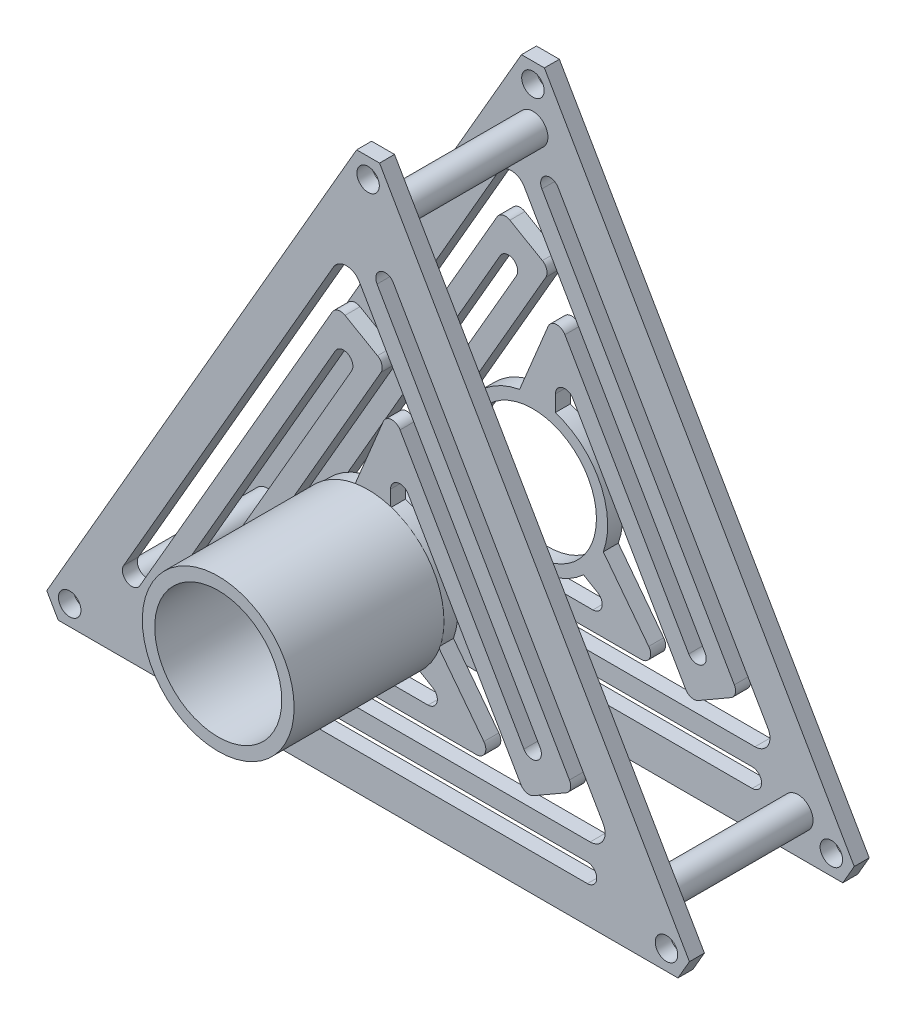
SolidWorks part; units mm, degrees
ref_plane "Front Plane" through (0, 0, 0) normal (0, 0, 1) x (1, 0, 0)
ref_plane "Top Plane" through (0, 0, 0) normal (0, 1, 0) x (1, 0, 0)
ref_plane "Right Plane" through (0, 0, 0) normal (1, 0, 0) x (0, 0, -1)
sketch "Sketch2" plane through (0, 0, 0) normal (0, 0, 1) x (1, 0, 0)
  line L0 (-1.53, 48.6355) -> (1.53, 48.6355)
  line L1 (1.53, 48.6355) -> (42.8846, -22.9927)
  line L2 (42.8846, -22.9927) -> (41.3546, -25.6427)
  line L3 (41.3546, -25.6427) -> (-41.3546, -25.6427)
  line L4 (-41.3546, -25.6427) -> (-42.8845, -22.9927)
  line L5 (-42.8845, -22.9927) -> (-1.53, 48.6355)
  line L7 (-41.1236, -23.7427) -> (-38.5255, -22.2427)
  line L8 (8.6257, -8.4442) -> (6.7534, -7.3449)
  line L9 (8.0007, -10.7767) -> (-22.0968, -10.7767)
  line L10 (-18.5968, -15.7767) -> (29.6355, -15.7767)
  line L11 (15.4531, -11.2658) -> (9.3926, -3.3669)
  line L12 (-23.3468, -12.0267) -> (-23.3468, -17.0267)
  line L13 (-22.0968, -18.2767) -> (29.2646, -18.2767)
  line L14 (29.2646, -20.7767) -> (-26.7487, -20.7767)
  line L15 (14.4613, -13.2767) -> (-18.5968, -13.2767)
  line L17 (-32.6255, -14.9556) -> (-4.6188, 33.5534)
  line L18 (-4.7797, 28.2747) -> (-30.4604, -16.2056)
  line L19 (1.258, 26.2323) -> (-3.0722, 28.7323)
  line L20 (-13.3333, -1.5405) -> (1.7155, 24.5247)
  line L21 (-18.7286, -5.8855) -> (-2.1996, 22.7436)
  line L22 (-4.3646, 23.9936) -> (-28.4808, -17.7767)
  line L23 (-17.483, -7.7498) -> (-7.6121, -6.4508)
  line L24 (-11.6257, -3.248) -> (-9.7376, -2.1762)
  line L25 (3.3608, 35.7323) -> (31.3675, -12.7767)
  line L26 (26.8765, -9.998) -> (1.1958, 34.4823)
  line L27 (22.0888, -14.2056) -> (26.419, -11.7056)
  line L28 (5.3325, 12.3172) -> (20.3813, -13.748)
  line L29 (4.2673, 19.1622) -> (20.7964, -9.4669)
  line L30 (22.9614, -8.2169) -> (-1.1547, 33.5534)
  line L31 (2.0299, 19.0156) -> (-1.7805, 9.8176)
  line L32 (3, 11.6922) -> (2.9842, 9.5211)
  circle A0 centre (-39.8246, -22.9927) radius 1.5
  circle A1 centre (0, 0) radius 8.4762
  arc A2 (-1.7805, 9.8176) -> (-9.7376, -2.1762) centre (0, 0) ccw
  arc A3 (8.6257, -8.4442) -> (8.0007, -10.7767) centre (7.9916, -9.5243) cw
  arc A4 (-22.0968, -10.7767) -> (-23.3468, -12.0267) centre (-22.0968, -12.0267) ccw
  arc A5 (-23.3468, -17.0267) -> (-22.0968, -18.2767) centre (-22.0968, -17.0267) ccw
  arc A6 (29.2646, -18.2767) -> (29.2646, -20.7767) centre (29.2646, -19.5267) cw
  circle A7 centre (0, 45.9855) radius 1.5
  arc A8 (15.4531, -11.2658) -> (14.4613, -13.2767) centre (14.4613, -12.0267) cw
  arc A9 (-18.5968, -13.2767) -> (-18.5968, -15.7767) centre (-18.5968, -14.5267) ccw
  arc A10 (-30.4604, -16.2056) -> (-32.6255, -14.9556) centre (-31.5429, -15.5806) cw
  arc A11 (-3.0722, 28.7323) -> (-4.7797, 28.2747) centre (-3.6972, 27.6497) ccw
  arc A12 (1.7155, 24.5247) -> (1.258, 26.2323) centre (0.633, 25.1497) ccw
  arc A13 (-2.1996, 22.7436) -> (-4.3646, 23.9936) centre (-3.2821, 23.3686) ccw
  arc A14 (-17.483, -7.7498) -> (-18.7286, -5.8855) centre (-17.6461, -6.5105) cw
  arc A15 (-11.6257, -3.248) -> (-13.3333, -1.5405) centre (-12.2441, -2.1588) cw
  circle A16 centre (39.8246, -22.9927) radius 1.5
  arc A17 (1.1958, 34.4823) -> (3.3608, 35.7323) centre (2.2783, 35.1073) cw
  arc A18 (26.419, -11.7056) -> (26.8765, -9.998) centre (25.794, -10.623) ccw
  arc A19 (20.3813, -13.748) -> (22.0888, -14.2056) centre (21.4638, -13.123) ccw
  arc A20 (20.7964, -9.4669) -> (22.9614, -8.2169) centre (21.8789, -8.8419) ccw
  arc A21 (2.0299, 19.0156) -> (4.2673, 19.1622) centre (3.1848, 18.5372) cw
  arc A22 (3, 11.6922) -> (5.3325, 12.3172) centre (4.2524, 11.6831) cw
  arc A23 (-26.7487, -20.7767) -> (-28.4808, -17.7767) centre (-26.7487, -18.7767) cw
  arc A24 (29.6355, -15.7767) -> (31.3675, -12.7767) centre (29.6355, -13.7767) ccw
  arc A25 (-4.6188, 33.5534) -> (-1.1547, 33.5534) centre (-2.8868, 32.5534) cw
  arc A26 (-7.6121, -6.4508) -> (6.7534, -7.3449) centre (0, 0) ccw
  arc A27 (9.3926, -3.3669) -> (2.9842, 9.5211) centre (0, 0) ccw
  point P31 (-90.3022, 1.3118)
  point P112 (0, 0)
  dimension "D2" = 2
  dimension "D3" = 2
  dimension "D4" = 2
  dimension "D1" = 3
extrude "Boss-Extrude1" add sketch "Sketch2" along normal blind 2 contours L5 L4 L3 L2 L1 L0 A16 A7 A1 A0 L17 A25 L30 A20 L29 A21 L31 A2 L24 A15 L20 A12 L19 A11 L18 A10 L23 A26 L8 A3 L9 A4 L12 A5 L13 A6 L14 A23 L22 A13 L21 A14 L11
sketch "Sketch3" plane through (0, 0, 2) normal (0, 0, 1) x (1, 0, 0)
  line L0 (-1.53, 48.6355) -> (1.53, 48.6355)
  line L1 (1.53, 48.6355) -> (42.8846, -22.9927)
  line L2 (42.8846, -22.9927) -> (41.3546, -25.6427)
  line L3 (41.3546, -25.6427) -> (-41.3546, -25.6427)
  line L4 (-41.3546, -25.6427) -> (-42.8845, -22.9927)
  line L5 (-42.8845, -22.9927) -> (-1.53, 48.6355)
  line L6 (-41.1236, -23.7427) -> (-38.5255, -22.2427)
  line L7 (8.6257, -8.4442) -> (6.7534, -7.3449)
  line L8 (8.0007, -10.7767) -> (-22.0968, -10.7767)
  line L9 (-18.5968, -15.7767) -> (29.6355, -15.7767)
  line L10 (15.4531, -11.2658) -> (9.3926, -3.3669)
  line L11 (-23.3468, -12.0267) -> (-23.3468, -17.0267)
  line L12 (-22.0968, -18.2767) -> (29.2646, -18.2767)
  line L13 (29.2646, -20.7767) -> (-26.7487, -20.7767)
  line L14 (14.4613, -13.2767) -> (-18.5968, -13.2767)
  line L15 (-32.6255, -14.9556) -> (-4.6188, 33.5534)
  line L16 (-4.7797, 28.2747) -> (-30.4604, -16.2056)
  line L17 (1.258, 26.2323) -> (-3.0722, 28.7323)
  line L18 (-13.3333, -1.5405) -> (1.7155, 24.5247)
  line L19 (-18.7286, -5.8855) -> (-2.1996, 22.7436)
  line L20 (-4.3646, 23.9936) -> (-28.4808, -17.7767)
  line L21 (-17.483, -7.7498) -> (-7.6121, -6.4508)
  line L22 (-11.6257, -3.248) -> (-9.7376, -2.1762)
  line L23 (3.3608, 35.7323) -> (31.3675, -12.7767)
  line L24 (26.8765, -9.998) -> (1.1958, 34.4823)
  line L25 (22.0888, -14.2056) -> (26.419, -11.7056)
  line L26 (5.3325, 12.3172) -> (20.3813, -13.748)
  line L27 (4.2673, 19.1622) -> (20.7964, -9.4669)
  line L28 (22.9614, -8.2169) -> (-1.1547, 33.5534)
  line L29 (2.0299, 19.0156) -> (-1.7805, 9.8176)
  line L30 (3, 11.6922) -> (2.9842, 9.5211)
  circle A2 centre (-39.8246, -22.9927) radius 1.5
  circle A3 centre (0, 0) radius 8.4762
  arc A4 (-1.7805, 9.8176) -> (-9.7376, -2.1762) centre (0, 0) ccw
  arc A5 (8.6257, -8.4442) -> (8.0007, -10.7767) centre (7.9916, -9.5243) cw
  arc A6 (-22.0968, -10.7767) -> (-23.3468, -12.0267) centre (-22.0968, -12.0267) ccw
  arc A7 (-23.3468, -17.0267) -> (-22.0968, -18.2767) centre (-22.0968, -17.0267) ccw
  arc A8 (29.2646, -18.2767) -> (29.2646, -20.7767) centre (29.2646, -19.5267) cw
  circle A9 centre (0, 45.9855) radius 1.5
  arc A10 (15.4531, -11.2658) -> (14.4613, -13.2767) centre (14.4613, -12.0267) cw
  arc A11 (-18.5968, -13.2767) -> (-18.5968, -15.7767) centre (-18.5968, -14.5267) ccw
  arc A12 (-30.4604, -16.2056) -> (-32.6255, -14.9556) centre (-31.5429, -15.5806) cw
  arc A13 (-3.0722, 28.7323) -> (-4.7797, 28.2747) centre (-3.6972, 27.6497) ccw
  arc A14 (1.7155, 24.5247) -> (1.258, 26.2323) centre (0.633, 25.1497) ccw
  arc A15 (-2.1996, 22.7436) -> (-4.3646, 23.9936) centre (-3.2821, 23.3686) ccw
  arc A16 (-17.483, -7.7498) -> (-18.7286, -5.8855) centre (-17.6461, -6.5105) cw
  arc A17 (-11.6257, -3.248) -> (-13.3333, -1.5405) centre (-12.2441, -2.1588) cw
  circle A18 centre (39.8246, -22.9927) radius 1.5
  arc A19 (1.1958, 34.4823) -> (3.3608, 35.7323) centre (2.2783, 35.1073) cw
  arc A20 (26.419, -11.7056) -> (26.8765, -9.998) centre (25.794, -10.623) ccw
  arc A21 (20.3813, -13.748) -> (22.0888, -14.2056) centre (21.4638, -13.123) ccw
  arc A22 (20.7964, -9.4669) -> (22.9614, -8.2169) centre (21.8789, -8.8419) ccw
  arc A23 (2.0299, 19.0156) -> (4.2673, 19.1622) centre (3.1848, 18.5372) cw
  arc A24 (3, 11.6922) -> (5.3325, 12.3172) centre (4.2524, 11.6831) cw
  arc A25 (-26.7487, -20.7767) -> (-28.4808, -17.7767) centre (-26.7487, -18.7767) cw
  arc A26 (29.6355, -15.7767) -> (31.3675, -12.7767) centre (29.6355, -13.7767) ccw
  arc A27 (-4.6188, 33.5534) -> (-1.1547, 33.5534) centre (-2.8868, 32.5534) cw
  arc A28 (-7.6121, -6.4508) -> (6.7534, -7.3449) centre (0, 0) ccw
  arc A29 (9.3926, -3.3669) -> (2.9842, 9.5211) centre (0, 0) ccw
  circle A30 centre (-35.3834, -20.4286) radius 2
  circle A31 centre (0, 40.8573) radius 2
  circle A32 centre (35.3834, -20.4286) radius 2
  point P89 (0, 0)
  point P95 (0, 0)
  dimension "D1" = 2
  dimension "D2" = 2
  dimension "D3" = 2
extrude "Boss-Extrude4" add sketch "Sketch3" along normal blind 20 contours A30 | A32 | A31
sketch "Sketch5" plane through (0, 0, 22) normal (0, 0, 1) x (1, 0, 0)
  line L0 (-1.53, 48.6355) -> (1.53, 48.6355)
  line L1 (1.53, 48.6355) -> (42.8846, -22.9927)
  line L2 (42.8846, -22.9927) -> (41.3546, -25.6427)
  line L3 (41.3546, -25.6427) -> (-41.3546, -25.6427)
  line L4 (-41.3546, -25.6427) -> (-42.8845, -22.9927)
  line L5 (-42.8845, -22.9927) -> (-1.53, 48.6355)
  line L6 (-41.1236, -23.7427) -> (-38.5255, -22.2427)
  line L7 (8.6257, -8.4442) -> (6.7534, -7.3449)
  line L8 (8.0007, -10.7767) -> (-22.0968, -10.7767)
  line L9 (-18.5968, -15.7767) -> (29.6355, -15.7767)
  line L10 (15.4531, -11.2658) -> (9.3926, -3.3669)
  line L11 (-23.3468, -12.0267) -> (-23.3468, -17.0267)
  line L12 (-22.0968, -18.2767) -> (29.2646, -18.2767)
  line L13 (29.2646, -20.7767) -> (-26.7487, -20.7767)
  line L14 (14.4613, -13.2767) -> (-18.5968, -13.2767)
  line L15 (-32.6255, -14.9556) -> (-4.6188, 33.5534)
  line L16 (-4.7797, 28.2747) -> (-30.4604, -16.2056)
  line L17 (1.258, 26.2323) -> (-3.0722, 28.7323)
  line L18 (-13.3333, -1.5405) -> (1.7155, 24.5247)
  line L19 (-18.7286, -5.8855) -> (-2.1996, 22.7436)
  line L20 (-4.3646, 23.9936) -> (-28.4808, -17.7767)
  line L21 (-17.483, -7.7498) -> (-7.6121, -6.4508)
  line L22 (-11.6257, -3.248) -> (-9.7376, -2.1762)
  line L23 (3.3608, 35.7323) -> (31.3675, -12.7767)
  line L24 (26.8765, -9.998) -> (1.1958, 34.4823)
  line L25 (22.0888, -14.2056) -> (26.419, -11.7056)
  line L26 (5.3325, 12.3172) -> (20.3813, -13.748)
  line L27 (4.2673, 19.1622) -> (20.7964, -9.4669)
  line L28 (22.9614, -8.2169) -> (-1.1547, 33.5534)
  line L29 (2.0299, 19.0156) -> (-1.7805, 9.8176)
  line L30 (3, 11.6922) -> (2.9842, 9.5211)
  circle A0 centre (-39.8246, -22.9927) radius 1.5
  circle A1 centre (0, 0) radius 8.4762
  arc A2 (-1.7805, 9.8176) -> (-9.7376, -2.1762) centre (0, 0) ccw
  arc A3 (8.6257, -8.4442) -> (8.0007, -10.7767) centre (7.9916, -9.5243) cw
  arc A4 (-22.0968, -10.7767) -> (-23.3468, -12.0267) centre (-22.0968, -12.0267) ccw
  arc A5 (-23.3468, -17.0267) -> (-22.0968, -18.2767) centre (-22.0968, -17.0267) ccw
  arc A6 (29.2646, -18.2767) -> (29.2646, -20.7767) centre (29.2646, -19.5267) cw
  circle A7 centre (0, 45.9855) radius 1.5
  arc A8 (15.4531, -11.2658) -> (14.4613, -13.2767) centre (14.4613, -12.0267) cw
  arc A9 (-18.5968, -13.2767) -> (-18.5968, -15.7767) centre (-18.5968, -14.5267) ccw
  arc A10 (-30.4604, -16.2056) -> (-32.6255, -14.9556) centre (-31.5429, -15.5806) cw
  arc A11 (-3.0722, 28.7323) -> (-4.7797, 28.2747) centre (-3.6972, 27.6497) ccw
  arc A12 (1.7155, 24.5247) -> (1.258, 26.2323) centre (0.633, 25.1497) ccw
  arc A13 (-2.1996, 22.7436) -> (-4.3646, 23.9936) centre (-3.2821, 23.3686) ccw
  arc A14 (-17.483, -7.7498) -> (-18.7286, -5.8855) centre (-17.6461, -6.5105) cw
  arc A15 (-11.6257, -3.248) -> (-13.3333, -1.5405) centre (-12.2441, -2.1588) cw
  circle A16 centre (39.8246, -22.9927) radius 1.5
  arc A17 (1.1958, 34.4823) -> (3.3608, 35.7323) centre (2.2783, 35.1073) cw
  arc A18 (26.419, -11.7056) -> (26.8765, -9.998) centre (25.794, -10.623) ccw
  arc A19 (20.3813, -13.748) -> (22.0888, -14.2056) centre (21.4638, -13.123) ccw
  arc A20 (20.7964, -9.4669) -> (22.9614, -8.2169) centre (21.8789, -8.8419) ccw
  arc A21 (2.0299, 19.0156) -> (4.2673, 19.1622) centre (3.1848, 18.5372) cw
  arc A22 (3, 11.6922) -> (5.3325, 12.3172) centre (4.2524, 11.6831) cw
  arc A23 (-26.7487, -20.7767) -> (-28.4808, -17.7767) centre (-26.7487, -18.7767) cw
  arc A24 (29.6355, -15.7767) -> (31.3675, -12.7767) centre (29.6355, -13.7767) ccw
  arc A25 (-4.6188, 33.5534) -> (-1.1547, 33.5534) centre (-2.8868, 32.5534) cw
  arc A26 (-7.6121, -6.4508) -> (6.7534, -7.3449) centre (0, 0) ccw
  arc A27 (9.3926, -3.3669) -> (2.9842, 9.5211) centre (0, 0) ccw
  circle A28 centre (-35.3834, -20.4286) radius 2
  circle A29 centre (0, 40.8573) radius 2
  circle A30 centre (35.3834, -20.4286) radius 2
  point P86 (0, 0)
  point P92 (0, 0)
  circle M23 centre (0, 40.8573) radius 2
extrude "Boss-Extrude5" add sketch "Sketch5" along normal blind 2 contours L5 L4 L3 L2 L1 L0 A30 A28 A16 A7 A1 A0 L15 A25 L28 A20 L27 A21 L29 A2 L22 A15 L18 A12 L17 A11 L16 A10 L21 A26 L7 A3 L8 A4 L11 A5 L12 A6 L13 A23 M23 | M23 | A30 | A28
sketch "Sketch6" plane through (0, 0, 24) normal (0, 0, 1) x (1, 0, 0)
  circle A0 centre (0, 0) radius 8.4762
  circle A1 centre (0, 0) radius 10.1303
extrude "Boss-Extrude6" add sketch "Sketch6" along normal blind 20
